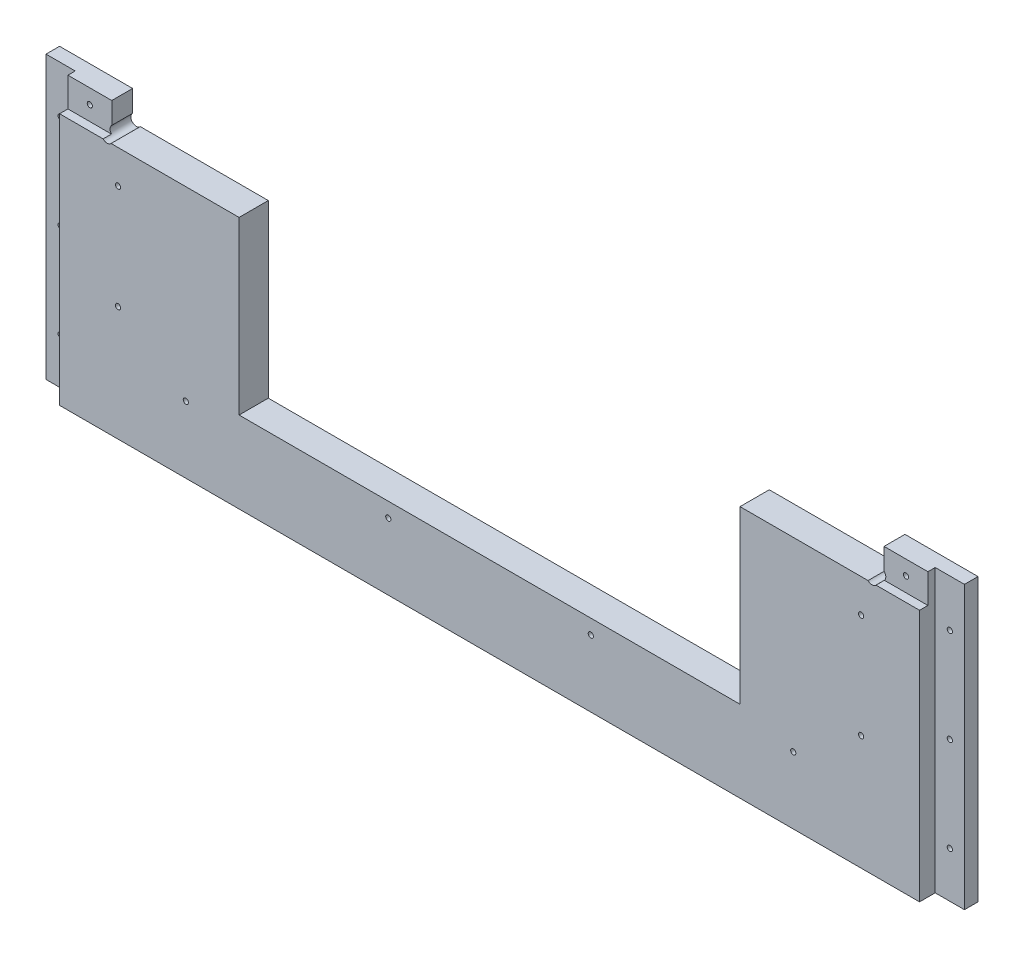
SolidWorks part; units mm, degrees
material "Pine"
ref_plane "Front Plane" through (0, 0, 0) normal (0, 0, 1) x (1, 0, 0)
ref_plane "Top Plane" through (0, 0, 0) normal (0, 1, 0) x (1, 0, 0)
ref_plane "Right Plane" through (0, 0, 0) normal (1, 0, 0) x (0, 0, -1)
sketch "Sketch1" plane through (0, 0, 0) normal (0, 0, 1) x (1, 0, 0)
  line L0 (8932.6508, -5243.5125) -> (10226.1458, -5243.5125)
  line L1 (9086.3208, -4722.0918) -> (10222.9708, -4853.7812)
  line L2 (8914.8708, -6342.0625) -> (10197.5708, -6342.0625)
  line L3 (8914.8708, -5808.6625) -> (10197.5708, -5808.6625)
  line L4 (8919.6333, -5253.0375) -> (10218.2083, -5253.0375)
  line L5 (9134.2633, -4656.1375) -> (9134.2633, -4638.3575)
  line L6 (9091.0833, -4638.3575) -> (9134.2633, -4638.3575)
  line L7 (9091.0833, -4567.2375) -> (9091.0833, -4638.3575)
  line L8 (9134.2633, -4656.1375) -> (9581.3033, -4656.1375)
  line L9 (9091.0833, -4567.2375) -> (9624.4833, -4567.2375)
  line L10 (9581.3033, -4656.1375) -> (9581.3033, -4638.3575)
  line L11 (9581.3033, -4638.3575) -> (9624.4833, -4638.3575)
  line L12 (9624.4833, -4567.2375) -> (9624.4833, -4638.3575)
  line L13 (8932.6508, -5225.7325) -> (9344.9775, -5225.7325)
  line L14 (8932.6508, -5256.2125) -> (8932.6508, -5243.5125)
  line L15 (8911.6958, -5256.2125) -> (8932.6508, -5256.2125)
  line L16 (8914.8708, -4722.0918) -> (9086.3208, -4722.0918)
  line L17 (8911.6958, -4715.5913) -> (8932.6508, -4715.5913)
  line L18 (8914.8708, -6342.0625) -> (8914.8708, -5808.6625)
  line L19 (12082.9917, -4722.0918) -> (10946.3417, -4853.7812)
  line L20 (12236.6617, -5243.5125) -> (10943.1667, -5243.5125)
  line L21 (10951.1042, -5253.0375) -> (12249.6792, -5253.0375)
  line L22 (10838.3917, -5656.2625) -> (11308.2917, -5656.2625)
  line L23 (10838.3917, -5719.7625) -> (11308.2917, -5719.7625)
  line L24 (10838.3917, -5742.5368) -> (11308.2917, -5742.5368)
  line L25 (10806.6417, -6342.0625) -> (11340.0417, -6342.0625)
  line L26 (10803.4667, -6335.7125) -> (11343.2167, -6335.7125)
  line L27 (10803.4667, -6317.9325) -> (11343.2167, -6317.9325)
  line L28 (10943.1667, -5225.7325) -> (11376.4483, -5225.7325)
  line L29 (11506.7292, -4754.5625) -> (10806.6417, -4827.5875)
  line L30 (11506.7292, -4567.2375) -> (11506.7292, -4754.5625)
  line L31 (10806.6417, -4567.2375) -> (10806.6417, -4827.5875)
  line L32 (10806.6417, -4567.2375) -> (11506.7292, -4567.2375)
  line L33 (10235.6708, -6329.3625) -> (10245.1958, -6329.3625)
  line L34 (10245.1958, -6329.3625) -> (10254.7208, -6278.5625)
  line L35 (10302.3458, -6329.3625) -> (10311.8708, -6278.5625)
  line L36 (10302.3458, -6329.3625) -> (10292.8208, -6329.3625)
  line L37 (10245.1958, -5821.3625) -> (10254.7208, -5872.1625)
  line L38 (10235.6708, -5821.3625) -> (10245.1958, -5821.3625)
  line L39 (10292.8208, -5821.3625) -> (10302.3458, -5821.3625)
  line L40 (10302.3458, -5821.3625) -> (10311.8708, -5872.1625)
  line L41 (10235.6708, -5821.3625) -> (10235.6708, -6329.3625)
  line L42 (10254.7208, -5872.1625) -> (10254.7208, -6278.5625)
  line L43 (10311.8708, -5872.1625) -> (10311.8708, -6278.5625)
  line L44 (10292.8208, -5821.3625) -> (10292.8208, -6329.3625)
  line L45 (8932.6508, -5225.7325) -> (8932.6508, -4715.5913)
  line L46 (8911.6958, -4715.5913) -> (8911.6958, -5256.2125)
  line L47 (8914.8708, -5248.275) -> (8914.8708, -4722.0918)
  line L48 (8919.6333, -5253.0375) -> (8914.8708, -5248.275)
  line L49 (8914.8708, -5145.0875) -> (8937.426, -5145.0875)
  line L50 (8914.8708, -5202.2375) -> (8937.426, -5202.2375)
  line L51 (10838.3917, -5656.2625) -> (10838.3917, -5719.7625)
  line L52 (10832.0417, -5736.1868) -> (10856.1717, -5736.1868)
  line L53 (10806.6417, -6342.0625) -> (10806.6417, -5818.7368)
  line L54 (10832.0417, -5649.9125) -> (10856.1717, -5649.9125)
  line L55 (10832.0417, -5726.1125) -> (10856.1717, -5726.1125)
  line L56 (10806.6417, -5818.7368) -> (10833.9015, -5818.7368)
  line L57 (10832.0417, -5806.0442) -> (10851.6815, -5806.0442)
  line L58 (10856.1717, -5801.5541) -> (10856.1717, -5736.1868)
  line L59 (10838.3917, -5814.2467) -> (10838.3917, -5742.5368)
  line L60 (10832.0417, -5806.0442) -> (10832.0417, -5736.1868)
  line L61 (10803.4667, -6317.9325) -> (10803.4667, -6335.7125)
  line L62 (10197.5708, -5808.6625) -> (10197.5708, -6342.0625)
  line L63 (9762.3842, -6348.4125) -> (9762.3842, -5802.3125)
  line L64 (9780.1642, -6348.4125) -> (9762.3842, -6348.4125)
  line L65 (9780.1642, -5802.3125) -> (9780.1642, -6348.4125)
  line L66 (9762.3842, -5802.3125) -> (9780.1642, -5802.3125)
  line L67 (9332.2775, -6348.4125) -> (9332.2775, -5802.3125)
  line L68 (9332.2775, -6348.4125) -> (9350.0575, -6348.4125)
  line L69 (9350.0575, -5802.3125) -> (9350.0575, -6348.4125)
  line L70 (9332.2775, -5802.3125) -> (9350.0575, -5802.3125)
  line L71 (9993.8374, -6061.075) -> (9993.8374, -6045.2418)
  line L72 (9998.5999, -6065.8375) -> (10014.4331, -6065.8375)
  line L73 (9998.5999, -6084.8875) -> (10014.4331, -6084.8875)
  line L74 (9993.8374, -6105.4832) -> (9993.8374, -6089.65)
  line L75 (9974.7874, -6105.4832) -> (9974.7874, -6089.65)
  line L76 (9954.1917, -6084.8875) -> (9970.0249, -6084.8875)
  line L77 (9974.7874, -6061.075) -> (9974.7874, -6045.2418)
  line L78 (9954.1917, -6065.8375) -> (9970.0249, -6065.8375)
  line L79 (10793.9417, -6237.2875) -> (10816.4969, -6237.2875)
  line L80 (10793.9417, -6294.4375) -> (10816.4969, -6294.4375)
  line L81 (10856.1717, -5649.9125) -> (10856.1717, -5726.1125)
  line L82 (10832.0417, -5726.1125) -> (10832.0417, -5649.9125)
  line L83 (10226.1458, -5225.7325) -> (10226.1458, -5243.5125)
  line L84 (10205.1908, -5257.8) -> (10205.1908, -4844.2499)
  line L85 (10230.9083, -4844.2499) -> (10230.9083, -5257.8)
  line L86 (10205.1908, -5257.8) -> (10230.9083, -5257.8)
  line L87 (10205.1908, -4844.2499) -> (10230.9083, -4844.2499)
  line L88 (10946.3417, -5176.8375) -> (10968.8969, -5176.8375)
  line L89 (9349.4676, -5141.9125) -> (9358.2674, -5141.9125)
  line L90 (10946.3417, -5119.6875) -> (10968.8969, -5119.6875)
  line L91 (9929.011, -4660.9635) -> (10066.0807, -4660.9635)
  line L92 (9929.011, -4678.7435) -> (10066.0807, -4678.7435)
  line L93 (10943.1667, -5225.7325) -> (10943.1667, -5243.5125)
  line L94 (10946.3417, -5248.275) -> (10951.1042, -5253.0375)
  line L95 (10946.3417, -5257.8063) -> (10946.3417, -4849.0188)
  line L96 (10964.1217, -5257.8) -> (10964.1217, -4844.2499)
  line L97 (10938.4042, -4844.2499) -> (10938.4042, -5257.8)
  line L98 (10938.4042, -5257.8) -> (10964.1217, -5257.8)
  line L99 (10964.1217, -4844.2499) -> (10938.4042, -4844.2499)
  line L100 (10344.8908, -4560.8875) -> (10369.0208, -4560.8875)
  line L101 (10344.8908, -4560.8875) -> (10369.0208, -4560.8875)
  line L102 (10800.2917, -4560.8875) -> (10824.4217, -4560.8875)
  line L103 (10200.4156, -5119.6875) -> (10222.9708, -5119.6875)
  line L104 (10200.4156, -5176.8375) -> (10222.9708, -5176.8375)
  line L105 (9344.9775, -5146.4026) -> (9344.9775, -5225.7325)
  line L106 (10344.8908, -4560.8875) -> (10344.8908, -4833.9375)
  line L107 (9792.8642, -5225.7325) -> (9792.8642, -5146.4026)
  line L108 (9362.7575, -5225.7325) -> (9775.0842, -5225.7325)
  line L109 (9680.3633, -4761.8396) -> (9680.3633, -4559.9604)
  line L110 (9656.2333, -4559.9604) -> (9680.3633, -4559.9604)
  line L111 (9656.2333, -4761.8396) -> (9680.3633, -4761.8396)
  line L112 (9656.2333, -4761.8396) -> (9656.2333, -4559.9604)
  line L113 (9779.5743, -5141.9125) -> (9788.374, -5141.9125)
  line L114 (10070.5708, -4665.4536) -> (10070.5708, -4674.2534)
  line L115 (9924.5208, -4674.2534) -> (9924.5208, -4665.4536)
  line L116 (12127.4417, -6188.3925) -> (12205.5015, -6188.3925)
  line L117 (12209.9917, -6170.6125) -> (12209.9917, -6183.9024)
  line L118 (9792.8642, -5225.7325) -> (10226.1458, -5225.7325)
  line L119 (9662.5833, -4754.5625) -> (10362.6708, -4827.5875)
  line L120 (9662.5833, -4567.2375) -> (9662.5833, -4754.5625)
  line L121 (10362.6708, -4567.2375) -> (10362.6708, -4827.5875)
  line L122 (9662.5833, -4567.2375) -> (10362.6708, -4567.2375)
  line L123 (10824.4217, -4833.9375) -> (10800.2917, -4833.9375)
  line L124 (10800.2917, -4833.9375) -> (10800.2917, -4560.8875)
  line L125 (10824.4217, -4560.8875) -> (10824.4217, -4833.9375)
  line L126 (10344.8908, -4833.9375) -> (10369.0208, -4833.9375)
  line L127 (10369.0208, -4833.9375) -> (10369.0208, -4560.8875)
  line L128 (10222.9708, -5248.275) -> (10218.2083, -5253.0375)
  line L129 (10222.9708, -5257.8063) -> (10222.9708, -4849.0188)
  line L130 (11734.6544, -5701.375) -> (11739.2301, -5701.375)
  line L131 (9362.7575, -5225.7325) -> (9362.7575, -5146.4026)
  line L132 (9775.0842, -5146.4026) -> (9775.0842, -5225.7325)
  line L133 (11761.3864, -5701.375) -> (11756.8282, -5701.375)
  line L134 (11734.6544, -5693.755) -> (11739.2301, -5693.755)
  line L135 (11761.4039, -5693.755) -> (11756.8282, -5693.755)
  line L136 (11734.6544, -5701.375) -> (11739.2301, -5701.375)
  line L137 (11744.3462, -5721.3024) -> (11744.3462, -5706.4179)
  line L138 (11751.7122, -5721.3024) -> (11751.7122, -5706.4179)
  line L139 (11740.0917, -6170.6125) -> (11740.0917, -6183.9024)
  line L140 (11689.2917, -6188.3925) -> (11822.6417, -6188.3925)
  line L141 (11689.2917, -6348.4093) -> (11689.2917, -6164.2657)
  line L142 (11689.2917, -6164.2657) -> (11746.4417, -6164.2657)
  line L143 (11746.4417, -6164.2657) -> (11746.4417, -6188.3925)
  line L144 (11689.2917, -6164.2657) -> (11746.4417, -6164.2657)
  line L145 (11340.0417, -5818.7368) -> (11340.0417, -6342.0625)
  line L146 (11290.5117, -5726.1125) -> (11314.6417, -5726.1125)
  line L147 (11290.5117, -5649.9125) -> (11290.5117, -5726.1125)
  line L148 (11340.0417, -5818.7368) -> (11312.7818, -5818.7368)
  line L149 (11314.6417, -5806.0442) -> (11295.0018, -5806.0442)
  line L150 (11290.5117, -5801.5541) -> (11290.5117, -5736.1868)
  line L151 (11308.2917, -5814.2467) -> (11308.2917, -5742.5368)
  line L152 (11314.6417, -5806.0442) -> (11314.6417, -5736.1868)
  line L153 (11290.5117, -5736.1868) -> (11314.6417, -5736.1868)
  line L154 (11848.0417, -6267.1325) -> (11962.3417, -6267.1325)
  line L155 (11962.3417, -6267.1325) -> (11962.3417, -6203.6325)
  line L156 (11343.2167, -6317.9325) -> (11343.2167, -6335.7125)
  line L157 (11365.4417, -5656.2625) -> (11365.4417, -5719.7625)
  line L158 (11365.4417, -5656.2625) -> (11479.7417, -5656.2625)
  line L159 (11778.1917, -6071.3937) -> (11802.3217, -6071.3937)
  line L160 (11314.6417, -5726.1125) -> (11314.6417, -5649.9125)
  line L161 (11314.6417, -5649.9125) -> (11290.5117, -5649.9125)
  line L162 (11308.2917, -5719.7625) -> (11308.2917, -5656.2625)
  line L163 (11689.2917, -6348.4093) -> (11713.4217, -6348.4093)
  line L164 (12203.6417, -6164.2657) -> (12260.7917, -6164.2657)
  line L165 (11713.4217, -6348.4093) -> (11713.4217, -6164.2657)
  line L166 (11695.6417, -6342.0625) -> (11695.6417, -6170.6125)
  line L167 (11695.6417, -6048.5337) -> (11699.4517, -6052.3437)
  line L168 (11822.6417, -6292.5325) -> (11822.6417, -6188.3925)
  line L169 (11695.6417, -6342.0625) -> (11695.6417, -6170.6125)
  line L170 (11848.0417, -6203.6325) -> (11962.3417, -6203.6325)
  line L171 (11848.0417, -6203.6325) -> (11848.0417, -6267.1325)
  line L172 (11987.7417, -6267.1325) -> (11987.7417, -6203.6325)
  line L173 (11784.5417, -6077.7437) -> (11784.5417, -6141.2438)
  line L174 (11517.8417, -5656.2625) -> (11632.1417, -5656.2625)
  line L175 (11632.1417, -5656.2625) -> (11632.1417, -5719.7625)
  line L176 (11632.1417, -5719.7625) -> (11517.8417, -5719.7625)
  line L177 (11517.8417, -5719.7625) -> (11517.8417, -5656.2625)
  line L178 (11692.4667, -6028.2137) -> (11692.4667, -6045.9937)
  line L179 (11695.6417, -5979.3188) -> (11718.1969, -5979.3188)
  line L180 (11695.6417, -5922.1687) -> (11718.1969, -5922.1687)
  line L181 (11821.0415, -5722.9375) -> (11821.0415, -5943.6)
  line L182 (11687.7042, -5651.5) -> (11701.9917, -5651.5)
  line L183 (11687.7042, -5651.5) -> (11687.7042, -6055.5251)
  line L184 (11687.7042, -6055.5251) -> (11701.9917, -6055.5251)
  line L185 (11701.9917, -6055.5251) -> (11701.9917, -5651.5)
  line L186 (11695.6417, -6055.2013) -> (11695.6417, -5649.595)
  line L187 (11695.6417, -5656.2625) -> (11695.6417, -6048.5337)
  line L188 (11695.6417, -6170.6125) -> (11740.0917, -6170.6125)
  line L189 (12203.6417, -6164.2657) -> (12203.6417, -6188.3925)
  line L190 (12254.4417, -6342.0625) -> (12254.4417, -6170.6125)
  line L191 (12129.0419, -5943.6) -> (12129.0419, -5722.9375)
  line L192 (12254.4417, -6048.5337) -> (12250.6317, -6052.3437)
  line L193 (12257.6167, -6045.9937) -> (12257.6167, -6028.2137)
  line L194 (12248.0917, -5651.5) -> (12262.3792, -5651.5)
  line L195 (12262.3792, -5651.5) -> (12262.3792, -6055.5251)
  line L196 (12262.3792, -6055.5251) -> (12248.0917, -6055.5251)
  line L197 (12248.0917, -6055.5251) -> (12248.0917, -5651.5)
  line L198 (12254.4417, -6141.2438) -> (12254.4417, -6077.7437)
  line L199 (12236.6617, -6164.2657) -> (12260.7917, -6164.2657)
  line L200 (12102.0417, -6267.1325) -> (11987.7417, -6267.1325)
  line L201 (11330.1865, -6237.2875) -> (11352.7417, -6237.2875)
  line L202 (11330.1865, -6294.4375) -> (11352.7417, -6294.4375)
  line L203 (11474.6617, -5851.8425) -> (11492.4417, -5851.8425)
  line L204 (11474.6617, -5808.6625) -> (11474.6617, -5851.8425)
  line L205 (11403.5417, -5808.6625) -> (11474.6617, -5808.6625)
  line L206 (11492.4417, -5851.8425) -> (11492.4417, -6298.8825)
  line L207 (11403.5417, -6342.0625) -> (11403.5417, -5808.6625)
  line L208 (11474.6617, -6298.8825) -> (11492.4417, -6298.8825)
  line L209 (11474.6617, -6342.0625) -> (11474.6617, -6298.8825)
  line L210 (11403.5417, -6342.0625) -> (11474.6617, -6342.0625)
  line L211 (11619.4417, -5851.8425) -> (11601.6617, -5851.8425)
  line L212 (11601.6617, -5808.6625) -> (11601.6617, -5851.8425)
  line L213 (11530.5417, -5808.6625) -> (11601.6617, -5808.6625)
  line L214 (11619.4417, -5851.8425) -> (11619.4417, -6298.8825)
  line L215 (11530.5417, -6342.0625) -> (11530.5417, -5808.6625)
  line L216 (11619.4417, -6298.8825) -> (11601.6617, -6298.8825)
  line L217 (11601.6617, -6342.0625) -> (11601.6617, -6298.8825)
  line L218 (11530.5417, -6342.0625) -> (11601.6617, -6342.0625)
  line L219 (11479.7417, -5719.7625) -> (11479.7417, -5656.2625)
  line L220 (11365.4417, -5719.7625) -> (11479.7417, -5719.7625)
  line L221 (11778.1917, -6147.5937) -> (11802.3217, -6147.5937)
  line L222 (11802.3217, -6071.3937) -> (11802.3217, -6147.5937)
  line L223 (11778.1917, -6147.5937) -> (11778.1917, -6071.3937)
  line L224 (12254.4417, -5922.1687) -> (12231.8865, -5922.1687)
  line L225 (12254.4417, -5979.3188) -> (12231.8865, -5979.3188)
  line L226 (12254.4417, -6055.2013) -> (12254.4417, -5649.595)
  line L227 (12254.4417, -6048.5337) -> (12254.4417, -5656.2625)
  line L228 (11841.6917, -5702.2873) -> (12108.3917, -5702.2873)
  line L229 (11822.6417, -6292.5325) -> (12127.4417, -6292.5325)
  line L230 (12127.4417, -6292.5325) -> (12127.4417, -6188.3925)
  line L231 (12254.4417, -6170.6125) -> (12209.9917, -6170.6125)
  line L232 (11695.6417, -6342.0625) -> (12254.4417, -6342.0625)
  line L233 (12236.6617, -6348.4093) -> (12260.7917, -6348.4093)
  line L234 (12260.7917, -6348.4093) -> (12260.7917, -6164.2657)
  line L235 (12236.6617, -6348.4093) -> (12236.6617, -6164.2657)
  line L236 (12102.0417, -6203.6325) -> (12102.0417, -6267.1325)
  line L237 (11987.7417, -6203.6325) -> (12102.0417, -6203.6325)
  line L238 (12236.6617, -6147.5937) -> (12236.6617, -6071.3937)
  line L239 (12203.6417, -6188.3925) -> (12260.7917, -6188.3925)
  line L240 (11098.7417, -4665.4536) -> (11098.7417, -4674.2534)
  line L241 (11394.2283, -5146.4026) -> (11394.2283, -5225.7325)
  line L242 (11376.4483, -5225.7325) -> (11376.4483, -5146.4026)
  line L243 (11394.2283, -5225.7325) -> (11806.555, -5225.7325)
  line L244 (11841.6917, -5964.2502) -> (12108.3917, -5964.2502)
  line L245 (12236.6617, -6147.5937) -> (12260.7917, -6147.5937)
  line L246 (12236.6617, -5256.2125) -> (12236.6617, -5243.5125)
  line L247 (12260.7917, -6147.5937) -> (12260.7917, -6071.3937)
  line L248 (12260.7917, -6071.3937) -> (12236.6617, -6071.3937)
  line L249 (12254.4417, -6077.7437) -> (11784.5417, -6077.7437)
  line L250 (11784.5417, -6141.2438) -> (12254.4417, -6141.2438)
  line L252 (12254.4417, -5656.2625) -> (11695.6417, -5656.2625)
  line L253 (11699.4517, -6052.3437) -> (12250.6317, -6052.3437)
  line L254 (11692.4667, -6045.9937) -> (12257.6167, -6045.9937)
  line L255 (11692.4667, -6028.2137) -> (12257.6167, -6028.2137)
  line L256 (11824.335, -5146.4026) -> (11824.335, -5225.7325)
  line L257 (11811.0451, -5141.9125) -> (11819.8449, -5141.9125)
  line L258 (11244.7917, -4674.2534) -> (11244.7917, -4665.4536)
  line L259 (11806.555, -5225.7325) -> (11806.555, -5146.4026)
  line L260 (11488.9492, -4761.8396) -> (11488.9492, -4559.9604)
  line L261 (11488.9492, -4559.9604) -> (11513.0792, -4559.9604)
  line L262 (11488.9492, -4761.8396) -> (11513.0792, -4761.8396)
  line L263 (11513.0792, -4761.8396) -> (11513.0792, -4559.9604)
  line L264 (11240.3015, -4660.9635) -> (11103.2318, -4660.9635)
  line L265 (11103.2318, -4678.7435) -> (11240.3015, -4678.7435)
  line L266 (12236.6617, -5225.7325) -> (12236.6617, -4715.5913)
  line L267 (12257.6167, -4715.5913) -> (12257.6167, -5256.2125)
  line L268 (12254.4417, -5248.275) -> (12254.4417, -4722.0918)
  line L269 (12236.6617, -5225.7325) -> (11824.335, -5225.7325)
  line L270 (12035.0492, -4656.1375) -> (12035.0492, -4638.3575)
  line L271 (12078.2292, -4638.3575) -> (12035.0492, -4638.3575)
  line L272 (12078.2292, -4567.2375) -> (12078.2292, -4638.3575)
  line L273 (12035.0492, -4656.1375) -> (11588.0092, -4656.1375)
  line L274 (11544.8292, -4567.2375) -> (12078.2292, -4567.2375)
  line L275 (11588.0092, -4656.1375) -> (11588.0092, -4638.3575)
  line L276 (11544.8292, -4638.3575) -> (11588.0092, -4638.3575)
  line L277 (11544.8292, -4567.2375) -> (11544.8292, -4638.3575)
  line L278 (12249.6792, -5253.0375) -> (12254.4417, -5248.275)
  line L280 (12257.6167, -5256.2125) -> (12236.6617, -5256.2125)
  line L281 (12231.8865, -5145.0875) -> (12254.4417, -5145.0875)
  line L282 (12231.8865, -5202.2375) -> (12254.4417, -5202.2375)
  line L283 (12236.6617, -4715.5913) -> (12257.6167, -4715.5913)
  line L284 (12082.9917, -4722.0918) -> (12254.4417, -4722.0918)
  line L285 (11380.9385, -5141.9125) -> (11389.7382, -5141.9125)
  circle A0 centre (8923.7608, -4778.9042) radius 1.5875
  circle A1 centre (9062.6598, -4736.3765) radius 2.3685
  circle A2 centre (9051.3958, -6281.7375) radius 22.225
  circle A3 centre (9083.1458, -6249.9875) radius 1.5875
  circle A4 centre (9083.1458, -6313.4875) radius 1.5875
  circle A5 centre (9019.6458, -6249.9875) radius 1.5875
  circle A6 centre (9019.6458, -6313.4875) radius 1.5875
  circle A7 centre (8972.3383, -5202.2375) radius 1.5875
  circle A8 centre (8923.7608, -5015.9708) radius 1.5875
  circle A9 centre (8923.7608, -5134.5042) radius 1.5875
  circle A10 centre (9054.5708, -5234.6225) radius 1.5875
  circle A11 centre (8923.7608, -4897.4375) radius 1.5875
  circle A12 centre (8972.3383, -5087.9375) radius 1.5875
  circle A13 centre (8972.3383, -5145.0875) radius 1.5875
  circle A14 centre (10847.2817, -5668.9625) radius 1.5875
  circle A15 centre (10847.2817, -5707.0625) radius 1.5875
  circle A16 centre (10847.2817, -5755.2368) radius 1.5875
  circle A17 centre (10851.4092, -6237.2875) radius 1.5875
  circle A18 centre (10851.4092, -6294.4375) radius 1.5875
  circle A19 centre (10847.2817, -5793.3442) radius 1.5875
  arc A20 (10833.9015, -5818.7368) -> (10838.3917, -5814.2467) centre (10836.1466, -5816.4918) ccw
  arc A21 (10851.6815, -5806.0442) -> (10856.1717, -5801.5541) centre (10853.9266, -5803.7992) ccw
  circle A22 centre (10882.8417, -6040.4375) radius 1.5875
  circle A23 centre (10882.8417, -6218.2375) radius 1.5875
  circle A24 centre (10882.8417, -5862.6375) radius 1.5875
  circle A25 centre (10908.2417, -6326.8225) radius 1.5875
  circle A26 centre (10908.2417, -6326.8225) radius 1.5875
  circle A27 centre (10851.4092, -6180.1375) radius 1.5875
  circle A28 centre (10815.5317, -4783.4231) radius 1.5875
  circle A29 centre (10815.5317, -4696.9488) radius 1.5875
  circle A30 centre (10815.5317, -4610.4746) radius 1.5875
  circle A31 centre (10979.1323, -4867.0082) radius 2.3685
  circle A32 centre (10190.1802, -4867.0082) radius 2.3685
  circle A33 centre (10955.2317, -4929.9812) radius 1.5875
  circle A34 centre (10955.2317, -5031.5812) radius 1.5875
  circle A35 centre (10214.0808, -4929.9812) radius 1.5875
  circle A36 centre (10214.0808, -5031.5812) radius 1.5875
  circle A37 centre (9341.1675, -6265.8625) radius 1.5875
  circle A38 centre (9771.2742, -5884.8625) radius 1.5875
  circle A39 centre (9771.2742, -6138.8625) radius 1.5875
  circle A40 centre (9771.2742, -6011.8625) radius 1.5875
  arc A41 (10036.2287, -6113.8083) -> (10051.3426, -6111.6033) centre (10042.9639, -6107.0732) ccw
  arc A42 (10051.3426, -6111.6033) -> (10051.3426, -6039.1217) centre (9984.3124, -6075.3625) ccw
  arc A43 (10051.3426, -6039.1217) -> (10036.2287, -6036.9167) centre (10042.9639, -6043.6518) ccw
  arc A44 (10034.5851, -6102.5431) -> (10034.5851, -6048.1819) centre (9984.3124, -6075.3625) ccw
  arc A45 (10034.5851, -6102.5431) -> (10036.2287, -6113.8083) centre (10042.9639, -6107.0732) ccw
  arc A46 (10036.2287, -6036.9167) -> (10034.5851, -6048.1819) centre (10042.9639, -6043.6518) ccw
  arc A47 (9945.8666, -6127.2787) -> (9948.0717, -6142.3927) centre (9952.6018, -6134.0139) ccw
  arc A48 (9948.0717, -6142.3927) -> (10020.5532, -6142.3927) centre (9984.3124, -6075.3625) ccw
  arc A49 (10020.5532, -6142.3927) -> (10022.7583, -6127.2787) centre (10016.0231, -6134.0139) ccw
  arc A50 (9957.1319, -6125.6352) -> (10011.493, -6125.6352) centre (9984.3124, -6075.3625) ccw
  arc A51 (9957.1319, -6125.6352) -> (9945.8666, -6127.2787) centre (9952.6018, -6134.0139) ccw
  arc A52 (10022.7583, -6127.2787) -> (10011.493, -6125.6352) centre (10016.0231, -6134.0139) ccw
  arc A53 (9932.3962, -6036.9167) -> (9917.2822, -6039.1217) centre (9925.661, -6043.6518) ccw
  arc A54 (9917.2822, -6039.1217) -> (9917.2822, -6111.6033) centre (9984.3124, -6075.3625) ccw
  arc A55 (9917.2822, -6111.6033) -> (9932.3962, -6113.8083) centre (9925.661, -6107.0732) ccw
  arc A56 (9934.0398, -6048.1819) -> (9934.0398, -6102.5431) centre (9984.3124, -6075.3625) ccw
  arc A57 (9934.0398, -6048.1819) -> (9932.3962, -6036.9167) centre (9925.661, -6043.6518) ccw
  arc A58 (9932.3962, -6113.8083) -> (9934.0398, -6102.5431) centre (9925.661, -6107.0732) ccw
  arc A59 (9945.8666, -6023.4463) -> (9957.1319, -6025.0898) centre (9952.6018, -6016.7111) ccw
  arc A60 (10011.493, -6025.0898) -> (10022.7583, -6023.4463) centre (10016.0231, -6016.7111) ccw
  arc A61 (10011.493, -6025.0898) -> (9957.1319, -6025.0898) centre (9984.3124, -6075.3625) ccw
  arc A62 (9948.0717, -6008.3323) -> (9945.8666, -6023.4463) centre (9952.6018, -6016.7111) ccw
  arc A63 (10020.5532, -6008.3323) -> (9948.0717, -6008.3323) centre (9984.3124, -6075.3625) ccw
  arc A64 (10022.7583, -6023.4463) -> (10020.5532, -6008.3323) centre (10016.0231, -6016.7111) ccw
  arc A65 (10005.0943, -6187.7574) -> (10096.7073, -6096.1443) centre (9984.3124, -6075.3625) ccw
  arc A66 (9993.8374, -6178.3911) -> (10005.0943, -6187.7574) centre (10003.3624, -6178.3911) ccw
  arc A67 (10001.6306, -6169.0249) -> (10077.9748, -6092.6807) centre (9984.3124, -6075.3625) ccw
  arc A68 (10087.3411, -6084.8875) -> (10077.9748, -6092.6807) centre (10087.3411, -6094.4125) ccw
  arc A69 (10001.6306, -6169.0249) -> (9993.8374, -6178.3911) centre (10003.3624, -6178.3911) ccw
  arc A70 (9963.5306, -6187.7574) -> (9974.7874, -6178.3911) centre (9965.2624, -6178.3911) ccw
  arc A71 (9871.9176, -6096.1443) -> (9963.5306, -6187.7574) centre (9984.3124, -6075.3625) ccw
  arc A72 (9881.2838, -6084.8875) -> (9871.9176, -6096.1443) centre (9881.2838, -6094.4125) ccw
  arc A73 (9890.65, -6092.6807) -> (9966.9943, -6169.0249) centre (9984.3124, -6075.3625) ccw
  arc A74 (9974.7874, -6178.3911) -> (9966.9943, -6169.0249) centre (9965.2624, -6178.3911) ccw
  arc A75 (9890.65, -6092.6807) -> (9881.2838, -6084.8875) centre (9881.2838, -6094.4125) ccw
  arc A76 (9871.9176, -6054.5807) -> (9881.2838, -6065.8375) centre (9881.2838, -6056.3125) ccw
  arc A77 (9963.5306, -5962.9676) -> (9871.9176, -6054.5807) centre (9984.3124, -6075.3625) ccw
  arc A78 (9974.7874, -5972.3339) -> (9963.5306, -5962.9676) centre (9965.2624, -5972.3339) ccw
  arc A79 (9966.9943, -5981.7001) -> (9890.65, -6058.0443) centre (9984.3124, -6075.3625) ccw
  arc A80 (9881.2838, -6065.8375) -> (9890.65, -6058.0443) centre (9881.2838, -6056.3125) ccw
  arc A81 (9966.9943, -5981.7001) -> (9974.7874, -5972.3339) centre (9965.2624, -5972.3339) ccw
  arc A82 (10077.9748, -6058.0443) -> (10087.3411, -6065.8375) centre (10087.3411, -6056.3125) ccw
  arc A83 (9993.8374, -5972.3339) -> (10001.6306, -5981.7001) centre (10003.3624, -5972.3339) ccw
  arc A84 (10077.9748, -6058.0443) -> (10001.6306, -5981.7001) centre (9984.3124, -6075.3625) ccw
  arc A85 (10087.3411, -6065.8375) -> (10096.7073, -6054.5807) centre (10087.3411, -6056.3125) ccw
  arc A86 (10096.7073, -6054.5807) -> (10005.0943, -5962.9676) centre (9984.3124, -6075.3625) ccw
  arc A87 (10005.0943, -5962.9676) -> (9993.8374, -5972.3339) centre (10003.3624, -5972.3339) ccw
  arc A88 (10014.4331, -6065.8375) -> (10018.7361, -6059.0339) centre (10014.4331, -6061.075) ccw
  arc A89 (10018.7361, -6059.0339) -> (10000.641, -6040.9388) centre (9984.3124, -6075.3625) ccw
  arc A90 (10000.641, -6040.9388) -> (9993.8374, -6045.2418) centre (9998.5999, -6045.2418) ccw
  arc A91 (9993.8374, -6061.075) -> (9998.5999, -6065.8375) centre (9998.5999, -6061.075) ccw
  arc A92 (9993.8374, -6105.4832) -> (10000.641, -6109.7862) centre (9998.5999, -6105.4832) ccw
  arc A93 (10000.641, -6109.7862) -> (10018.7361, -6091.6911) centre (9984.3124, -6075.3625) ccw
  arc A94 (10018.7361, -6091.6911) -> (10014.4331, -6084.8875) centre (10014.4331, -6089.65) ccw
  arc A95 (9998.5999, -6084.8875) -> (9993.8374, -6089.65) centre (9998.5999, -6089.65) ccw
  arc A96 (9954.1917, -6084.8875) -> (9949.8888, -6091.6911) centre (9954.1917, -6089.65) ccw
  arc A97 (9949.8888, -6091.6911) -> (9967.9839, -6109.7862) centre (9984.3124, -6075.3625) ccw
  arc A98 (9967.9839, -6109.7862) -> (9974.7874, -6105.4832) centre (9970.0249, -6105.4832) ccw
  arc A99 (9974.7874, -6089.65) -> (9970.0249, -6084.8875) centre (9970.0249, -6089.65) ccw
  arc A100 (9970.0249, -6065.8375) -> (9974.7874, -6061.075) centre (9970.0249, -6061.075) ccw
  arc A101 (9949.8888, -6059.0339) -> (9954.1917, -6065.8375) centre (9954.1917, -6061.075) ccw
  arc A102 (9967.9839, -6040.9388) -> (9949.8888, -6059.0339) centre (9984.3124, -6075.3625) ccw
  arc A103 (9974.7874, -6045.2418) -> (9967.9839, -6040.9388) centre (9970.0249, -6045.2418) ccw
  arc A104 (10096.7073, -6096.1443) -> (10087.3411, -6084.8875) centre (10087.3411, -6094.4125) ccw
  circle A105 centre (9771.2742, -6265.8625) radius 1.5875
  circle A106 centre (9341.1675, -5884.8625) radius 1.5875
  circle A107 centre (9341.1675, -6138.8625) radius 1.5875
  circle A108 centre (9341.1675, -6011.8625) radius 1.5875
  circle A109 centre (11037.2315, -4887.5494) radius 15.0812
  arc A110 (9349.4676, -5141.9125) -> (9344.9775, -5146.4026) centre (9347.2226, -5144.1576) ccw
  arc A111 (9362.7575, -5146.4026) -> (9358.2674, -5141.9125) centre (9360.5124, -5144.1576) ccw
  circle A112 centre (9946.7458, -4669.8535) radius 1.5875
  arc A113 (9924.5208, -4674.2534) -> (9929.011, -4678.7435) centre (9926.7659, -4676.4984) ccw
  circle A114 centre (11003.8092, -5176.8375) radius 1.5875
  circle A115 centre (11003.8092, -5119.6875) radius 1.5875
  circle A116 centre (10353.7808, -4696.9488) radius 1.5875
  circle A117 centre (10353.7808, -4610.4746) radius 1.5875
  circle A118 centre (10353.7808, -4783.4231) radius 1.5875
  circle A119 centre (11003.8092, -5062.5375) radius 1.5875
  circle A120 centre (9353.8675, -5160.9625) radius 1.5875
  circle A121 centre (9638.7708, -5234.6225) radius 1.5875
  circle A122 centre (9671.4733, -4724.1144) radius 1.5875
  circle A123 centre (9671.4733, -4661.3637) radius 1.5875
  circle A124 centre (9671.4733, -4598.6129) radius 1.5875
  arc A125 (9792.8642, -5146.4026) -> (9788.374, -5141.9125) centre (9790.6191, -5144.1576) ccw
  arc A126 (9779.5743, -5141.9125) -> (9775.0842, -5146.4026) centre (9777.3292, -5144.1576) ccw
  circle A127 centre (10048.3458, -4669.8535) radius 1.5875
  arc A128 (10070.5708, -4665.4536) -> (10066.0807, -4660.9635) centre (10068.3258, -4663.2086) ccw
  arc A129 (10066.0807, -4678.7435) -> (10070.5708, -4674.2534) centre (10068.3258, -4676.4984) ccw
  circle A130 centre (9997.5458, -4669.8535) radius 1.5875
  arc A131 (9929.011, -4660.9635) -> (9924.5208, -4665.4536) centre (9926.7659, -4663.2086) ccw
  circle A132 centre (10132.081, -4887.5494) radius 15.0812
  circle A133 centre (10165.5033, -5176.8375) radius 1.5875
  circle A134 centre (10165.5033, -5119.6875) radius 1.5875
  circle A135 centre (9486.3708, -5234.6225) radius 1.5875
  circle A136 centre (10165.5033, -5062.5375) radius 1.5875
  circle A137 centre (9206.9708, -5234.6225) radius 1.5875
  circle A138 centre (10070.5708, -5234.6225) radius 1.5875
  circle A139 centre (9918.1708, -5234.6225) radius 1.5875
  circle A140 centre (9783.9742, -5160.9625) radius 1.5875
  circle A141 centre (9783.9742, -5193.9825) radius 1.5875
  circle A142 centre (9353.8675, -5193.9825) radius 1.5875
  circle A143 centre (11073.3417, -6326.8225) radius 1.5875
  circle A144 centre (11073.3417, -6326.8225) radius 1.5875
  circle A145 centre (11295.2742, -6180.1375) radius 1.5875
  circle A146 centre (11295.2742, -6294.4375) radius 1.5875
  circle A147 centre (11295.2742, -6237.2875) radius 1.5875
  circle A148 centre (11975.0417, -5692.775) radius 3.4925
  circle A149 centre (11263.8417, -5862.6375) radius 1.5875
  arc A150 (11739.2301, -5701.375) -> (11744.3462, -5706.4179) centre (11748.0292, -5697.565) ccw
  arc A151 (11751.7122, -5706.4179) -> (11756.8282, -5701.375) centre (11748.0292, -5697.565) ccw
  arc A152 (11744.3462, -5721.3024) -> (11751.7122, -5721.3024) centre (11748.0292, -5725.505) ccw
  arc A153 (11734.6544, -5693.755) -> (11724.9787, -5697.565) centre (11730.5667, -5697.565) ccw
  arc A154 (11756.8282, -5693.755) -> (11739.2301, -5693.755) centre (11748.0292, -5697.565) ccw
  arc A155 (11724.9787, -5697.565) -> (11734.6544, -5701.375) centre (11730.5667, -5697.565) ccw
  arc A156 (11761.3864, -5701.375) -> (11771.0797, -5697.565) centre (11765.4842, -5697.565) ccw
  arc A157 (11771.0797, -5697.565) -> (11761.4039, -5693.755) centre (11765.4917, -5697.565) ccw
  arc A158 (11740.0917, -6183.9024) -> (11744.5818, -6188.3925) centre (11742.3367, -6186.1474) ccw
  arc A159 (12205.5015, -6188.3925) -> (12209.9917, -6183.9024) centre (12207.7466, -6186.1474) ccw
  circle A160 centre (11299.4017, -5793.3442) radius 1.5875
  arc A161 (11308.2917, -5814.2467) -> (11312.7818, -5818.7368) centre (11310.5367, -5816.4918) ccw
  arc A162 (11290.5117, -5801.5541) -> (11295.0018, -5806.0442) centre (11292.7567, -5803.7992) ccw
  circle A163 centre (11704.5317, -6314.149) radius 1.5875
  circle A164 centre (11748.9817, -6208.7125) radius 1.5875
  circle A165 centre (11263.8417, -6218.2375) radius 1.5875
  circle A166 centre (11263.8417, -6040.4375) radius 1.5875
  circle A167 centre (11238.4417, -6326.8225) radius 1.5875
  circle A168 centre (11238.4417, -6326.8225) radius 1.5875
  circle A169 centre (11299.4017, -5668.9625) radius 1.5875
  circle A170 centre (11299.4017, -5707.0625) radius 1.5875
  circle A171 centre (11726.7567, -6179.5025) radius 1.5875
  circle A172 centre (11704.5317, -6199.3198) radius 1.5875
  circle A173 centre (11748.9817, -6272.2125) radius 1.5875
  circle A174 centre (11704.5317, -6256.7344) radius 1.5875
  circle A175 centre (11299.4017, -5755.2368) radius 1.5875
  circle A176 centre (11913.4467, -6301.4225) radius 1.5875
  circle A177 centre (11790.2567, -6301.4225) radius 1.5875
  circle A178 centre (11793.4317, -6128.5437) radius 1.5875
  circle A179 centre (11753.1092, -5865.0188) radius 1.5875
  circle A180 centre (11809.9417, -6037.1038) radius 1.5875
  circle A181 centre (11809.9417, -6037.1038) radius 1.5875
  circle A182 centre (11753.1092, -5922.1687) radius 1.5875
  circle A183 centre (11975.0417, -5973.7625) radius 3.4925
  circle A184 centre (11975.0417, -6037.1038) radius 1.5875
  circle A185 centre (11753.1092, -5979.3188) radius 1.5875
  circle A186 centre (11975.0417, -6037.1038) radius 1.5875
  arc A187 (11841.6917, -5702.2873) -> (11821.0415, -5722.9375) centre (11841.6917, -5722.9375) ccw
  circle A188 centre (11811.5292, -5833.2687) radius 3.4925
  arc A189 (11821.0415, -5943.6) -> (11841.6917, -5964.2502) centre (11841.6917, -5943.6) ccw
  circle A190 centre (12196.9742, -5865.0188) radius 1.5875
  arc A191 (12129.0419, -5722.9375) -> (12108.3917, -5702.2873) centre (12108.3917, -5722.9375) ccw
  circle A192 centre (12036.6367, -6301.4225) radius 1.5875
  circle A193 centre (12159.8267, -6301.4225) radius 1.5875
  circle A194 centre (12138.5542, -5833.2687) radius 3.4925
  circle A195 centre (12197.2917, -5761.0375) radius 15.0812
  circle A196 centre (11793.4317, -6090.4437) radius 1.5875
  circle A197 centre (12196.9742, -5922.1687) radius 1.5875
  arc A198 (12108.3917, -5964.2502) -> (12129.0419, -5943.6) centre (12108.3917, -5943.6) ccw
  circle A199 centre (12196.9742, -5979.3188) radius 1.5875
  circle A200 centre (12201.1017, -6272.2125) radius 1.5875
  circle A201 centre (12245.5517, -6314.149) radius 1.5875
  circle A202 centre (12245.5517, -6256.7344) radius 1.5875
  circle A203 centre (12201.1017, -6208.7125) radius 1.5875
  circle A204 centre (12223.3267, -6179.5025) radius 1.5875
  circle A205 centre (12245.5517, -6199.3198) radius 1.5875
  circle A206 centre (11171.7667, -4669.8535) radius 1.5875
  circle A207 centre (11222.5667, -4669.8535) radius 1.5875
  arc A208 (11240.3015, -4678.7435) -> (11244.7917, -4674.2534) centre (11242.5466, -4676.4984) ccw
  circle A209 centre (11385.3383, -5193.9825) radius 1.5875
  circle A210 centre (12106.6527, -4736.3765) radius 2.3685
  circle A211 centre (12140.1417, -6037.1038) radius 1.5875
  circle A212 centre (12140.1417, -6037.1038) radius 1.5875
  circle A213 centre (12245.5517, -6090.4437) radius 1.5875
  circle A214 centre (12245.5517, -6128.5437) radius 1.5875
  circle A215 centre (11385.3383, -5160.9625) radius 1.5875
  arc A216 (11824.335, -5146.4026) -> (11819.8449, -5141.9125) centre (11822.0899, -5144.1576) ccw
  arc A217 (11811.0451, -5141.9125) -> (11806.555, -5146.4026) centre (11808.8001, -5144.1576) ccw
  circle A218 centre (11815.445, -5193.9825) radius 1.5875
  circle A219 centre (11815.445, -5160.9625) radius 1.5875
  circle A220 centre (11530.5417, -5234.6225) radius 1.5875
  circle A221 centre (11962.3417, -5234.6225) radius 1.5875
  arc A222 (11244.7917, -4665.4536) -> (11240.3015, -4660.9635) centre (11242.5466, -4663.2086) ccw
  circle A223 centre (11682.9417, -5234.6225) radius 1.5875
  circle A224 centre (11497.8392, -4724.1144) radius 1.5875
  circle A225 centre (11497.8392, -4661.3637) radius 1.5875
  circle A226 centre (11497.8392, -4598.6129) radius 1.5875
  circle A227 centre (11120.9667, -4669.8535) radius 1.5875
  arc A228 (11103.2318, -4660.9635) -> (11098.7417, -4665.4536) centre (11100.9867, -4663.2086) ccw
  arc A229 (11098.7417, -4674.2534) -> (11103.2318, -4678.7435) centre (11100.9867, -4676.4984) ccw
  circle A230 centre (12196.9742, -5202.2375) radius 1.5875
  circle A231 centre (12245.5517, -5015.9708) radius 1.5875
  circle A232 centre (12245.5517, -5134.5042) radius 1.5875
  circle A233 centre (12114.7417, -5234.6225) radius 1.5875
  circle A234 centre (12245.5517, -4897.4375) radius 1.5875
  circle A235 centre (12245.5517, -4778.9042) radius 1.5875
  circle A236 centre (12196.9742, -5087.9375) radius 1.5875
  circle A237 centre (12196.9742, -5145.0875) radius 1.5875
  circle A238 centre (11098.7417, -5234.6225) radius 1.5875
  circle A239 centre (11251.1417, -5234.6225) radius 1.5875
  arc A240 (11380.9385, -5141.9125) -> (11376.4483, -5146.4026) centre (11378.6934, -5144.1576) ccw
  arc A241 (11394.2283, -5146.4026) -> (11389.7382, -5141.9125) centre (11391.9833, -5144.1576) ccw
sketch "Sketch2" plane through (0, 0, 0) normal (0, 0, 1) x (1, 0, 0)
  line L0 (12254.4417, -6342.0625) -> (12254.4417, -6170.6125)
  line L1 (12254.4417, -6170.6125) -> (12209.9917, -6170.6125)
  line L2 (12209.9917, -6170.6125) -> (12209.9917, -6188.3925)
  line L3 (12209.9917, -6188.3925) -> (12127.4417, -6188.3925)
  line L4 (12127.4417, -6188.3925) -> (12127.4417, -6292.5325)
  line L5 (12127.4417, -6292.5325) -> (11822.6417, -6292.5325)
  line L6 (11822.6417, -6292.5325) -> (11822.6417, -6188.3925)
  line L7 (11822.6417, -6188.3925) -> (11740.0917, -6188.3925)
  line L8 (11740.0917, -6188.3925) -> (11740.0917, -6170.6125)
  line L9 (11740.0917, -6170.6125) -> (11695.6417, -6170.6125)
  line L10 (11695.6417, -6170.6125) -> (11695.6417, -6342.0625)
  line L11 (11695.6417, -6342.0625) -> (12254.4417, -6342.0625)
  dimension "D1" = 17.78
  dimension "D2" = 104.14
  dimension "D3" = 17.78
extrude "Extrude1" add sketch "Sketch2" against normal blind 17.78
sketch "Sketch3" plane through (0, 0, 0) normal (0, 0, 1) x (1, 0, 0)
  line L0 (11740.0917, -6188.3925) -> (11740.0917, -6170.6125)
  line L1 (11740.0917, -6170.6125) -> (11695.6417, -6170.6125)
  line L2 (11695.6417, -6170.6125) -> (11695.6417, -6188.3925)
  line L3 (11695.6417, -6188.3925) -> (11740.0917, -6188.3925)
  line L4 (12209.9917, -6170.6125) -> (12254.4417, -6170.6125)
  line L5 (12254.4417, -6170.6125) -> (12254.4417, -6188.3925)
  line L6 (12254.4417, -6188.3925) -> (12209.9917, -6188.3925)
  line L7 (12209.9917, -6188.3925) -> (12209.9917, -6170.6125)
  line L8 (11695.6417, -6170.6125) -> (11695.6417, -6342.0625) construction
  line L9 (12254.4417, -6342.0625) -> (12254.4417, -6170.6125) construction
  line L10 (12209.9917, -6170.6125) -> (12209.9917, -6188.3925) construction
  line L11 (12209.9917, -6188.3925) -> (12127.4417, -6188.3925) construction
extrude "Cut-Extrude1" cut sketch "Sketch3" against normal blind 5.08
sketch "Sketch4" plane through (0, 0, 0) normal (0, 0, 1) x (1, 0, 0)
  line L0 (11695.6417, -6342.0625) -> (11713.4217, -6342.0625)
  line L1 (11713.4217, -6342.0625) -> (11713.4217, -6170.6125)
  line L2 (11713.4217, -6170.6125) -> (11695.6417, -6170.6125)
  line L3 (11695.6417, -6170.6125) -> (11695.6417, -6342.0625)
  line L4 (12236.6617, -6342.0625) -> (12254.4417, -6342.0625)
  line L5 (12254.4417, -6342.0625) -> (12254.4417, -6170.6125)
  line L6 (12254.4417, -6170.6125) -> (12236.6617, -6170.6125)
  line L7 (12236.6617, -6170.6125) -> (12236.6617, -6342.0625)
  line L8 (11695.6417, -6342.0625) -> (12254.4417, -6342.0625) construction
  line L9 (11695.6417, -6170.6125) -> (11740.0917, -6170.6125) construction
  line L10 (12254.4417, -6170.6125) -> (12209.9917, -6170.6125) construction
  dimension "D1" = 17.78
  dimension "D2" = 17.78
extrude "Cut-Extrude2" cut sketch "Sketch4" against normal blind 9.525
sketch "Sketch5" plane through (0, 0, 0) normal (0, 0, 1) x (1, 0, 0)
  line L0 (11740.0917, -6188.3925) -> (11742.3367, -6186.1474) construction
  line L1 (11822.6417, -6188.3925) -> (11713.4217, -6188.3925) construction
  line L2 (12209.9917, -6188.3925) -> (12207.7466, -6186.1474) construction
  line L3 (12236.6617, -6188.3925) -> (12127.4417, -6188.3925) construction
  circle A0 centre (11704.5317, -6314.149) radius 1.5875
  circle A1 centre (11704.5317, -6256.7344) radius 1.5875
  circle A2 centre (11704.5317, -6199.3198) radius 1.5875
  circle A3 centre (11726.7567, -6179.5025) radius 1.5875
  circle A4 centre (11748.9817, -6208.7125) radius 1.5875
  circle A5 centre (11748.9817, -6272.2125) radius 1.5875
  circle A6 centre (11790.2567, -6301.4225) radius 1.5875
  circle A7 centre (11913.4467, -6301.4225) radius 1.5875
  circle A8 centre (12036.6367, -6301.4225) radius 1.5875
  circle A9 centre (12159.8267, -6301.4225) radius 1.5875
  circle A10 centre (12245.5517, -6314.149) radius 1.5875
  circle A11 centre (12245.5517, -6256.7344) radius 1.5875
  circle A12 centre (12201.1017, -6272.2125) radius 1.5875
  circle A13 centre (12201.1017, -6208.7125) radius 1.5875
  circle A14 centre (12245.5517, -6199.3198) radius 1.5875
  circle A15 centre (12223.3267, -6179.5025) radius 1.5875
  circle A16 centre (11742.3367, -6186.1474) radius 3.302
  circle A17 centre (12207.7466, -6186.1474) radius 3.302
  dimension "D1" = 45
  dimension "D2" = 3.175
  dimension "D3" = 45
  dimension "D4" = 3.175
extrude "Cut-Extrude3" cut sketch "Sketch5" against normal up to surface (17.78 mm away)
